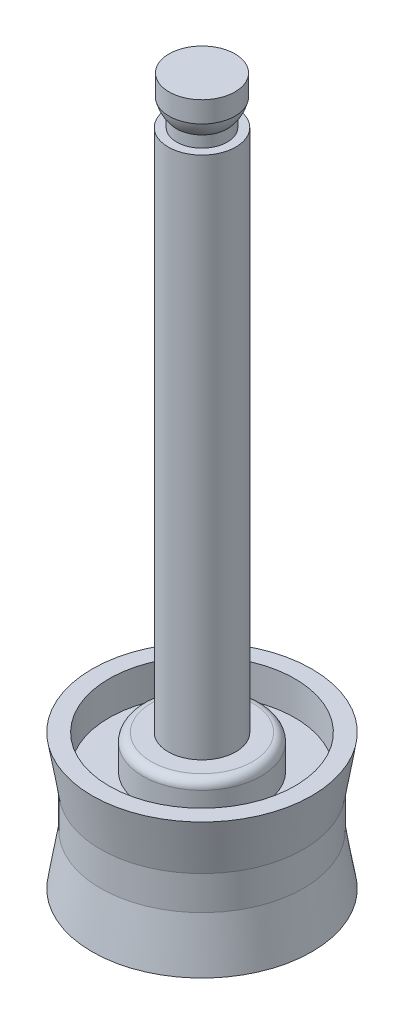
SolidWorks part; units mm, degrees
ref_plane "前视基准面" through (0, 0, 0) normal (0, 0, 1) x (1, 0, 0)
ref_plane "上视基准面" through (0, 0, 0) normal (0, 1, 0) x (1, 0, 0)
ref_plane "右视基准面" through (0, 0, 0) normal (1, 0, 0) x (0, 0, -1)
sketch "草图1" plane through (0, 0, 0) normal (0, 1, 0) x (1, 0, 0)
  circle A0 centre (0, 0) radius 6.5
  dimension "D1" = 13
extrude "凸台-拉伸1" add sketch "草图1" along normal blind 8
sketch "草图2" plane through (0, 8, 0) normal (0, 1, 0) x (1, 0, 0)
  circle A0 centre (0, 0) radius 2
  dimension "D1" = 4
extrude "凸台-拉伸2" add sketch "草图2" along normal blind 31
sketch "草图4" plane through (0, 0, 0) normal (0, 0, 1) x (1, 0, 0)
  line L0 (0, 39) -> (0, 41)
  line L1 (0, 41.8) -> (1.95, 41.8)
  line L2 (2, 39) -> (-2, 39) construction
  line L3 (0, 41) -> (0, 41.8)
  line L4 (1.95, 41.8) -> (1.95, 40.5556)
  line L5 (0, 39) -> (1.5, 39)
  line L6 (1.5, 39) -> (1.5, 39.6771)
  arc A1 (1.5, 39.6771) -> (1.95, 40.5556) centre (0, 41) ccw
  dimension "D5" = 2
  dimension "D1" = 2
  dimension "D2" = 0.8
  dimension "D3" = 1.95
  dimension "D4" = 1.5
revolve "旋转1" add sketch "草图4" angle 360 about L0
sketch "草图5" plane through (0, 0, 0) normal (0, 0, 1) x (1, 0, 0)
  line L0 (-6.5, 8) -> (-6.5, 5)
  line L1 (-6.5, 8) -> (-6.5, 0) construction
  line L2 (-6.5, 5) -> (-6.5, 3)
  line L3 (-6.5, 3) -> (-6.5, 0)
  line L4 (-6, 5) -> (-6, 3)
  line L5 (0, 0) -> (0, 8) construction
  line L6 (-6.5, 8) -> (-6, 5)
  line L7 (-6.5, 0) -> (-6, 3)
  line L8 (6.5, 8) -> (-6.5, 8) construction
  dimension "D1" = 3
  dimension "D2" = 3
  dimension "D3" = 0.5
  dimension "D4" = 0.5
revolve "切除-旋转1" cut sketch "草图5" angle 360 about L5
sketch "草图6" plane through (0, 0, 0) normal (0, -1, 0) x (1, 0, 0)
  circle A0 centre (0, 0) radius 3.5
  circle A1 centre (0, 0) radius 5.5
  dimension "D1" = 11
  dimension "D2" = 7
extrude "切除-拉伸1" cut sketch "草图6" against normal blind 2
sketch "草图7" plane through (0, 8, 0) normal (0, 1, 0) x (1, 0, 0)
  circle A0 centre (0, 0) radius 5.5
  circle A1 centre (0, 0) radius 3.5
  dimension "D1" = 11
  dimension "D2" = 7
extrude "切除-拉伸2" cut sketch "草图7" against normal blind 2
fillet "圆角2" radius 0.5 2 edges at (0, 0, -3.5) (0, 8, 3.5)
